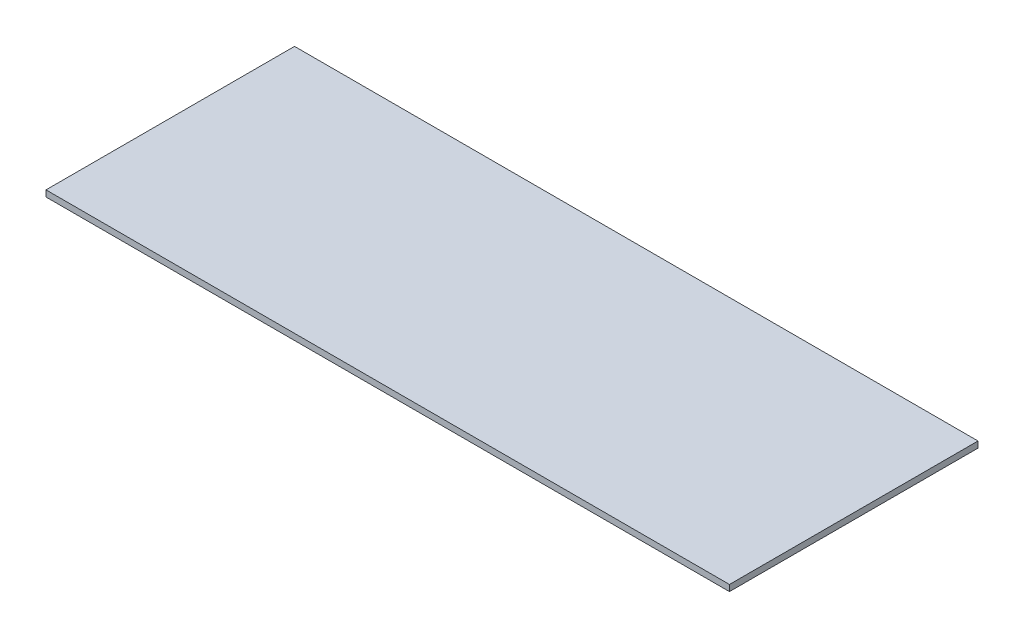
SolidWorks part; units mm, degrees
ref_plane "Front Plane" through (0, 0, 0) normal (0, 0, 1) x (1, 0, 0)
ref_plane "Top Plane" through (0, 0, 0) normal (0, 1, 0) x (1, 0, 0)
ref_plane "Right Plane" through (0, 0, 0) normal (1, 0, 0) x (0, 0, -1)
sketch "Sketch1" plane through (0, 0, 0) normal (0, 1, 0) x (1, 0, 0)
  line L1 (0, 0) -> (139.7, 0)
  line L2 (0, 0) -> (0, 50.8)
  line L3 (0, 50.8) -> (139.7, 50.8)
  line L4 (139.7, 0) -> (139.7, 50.8)
  dimension "D1" = 50.8
  dimension "D2" = 139.7
extrude "Boss-Extrude1" add sketch "Sketch1" along normal blind 1.27
